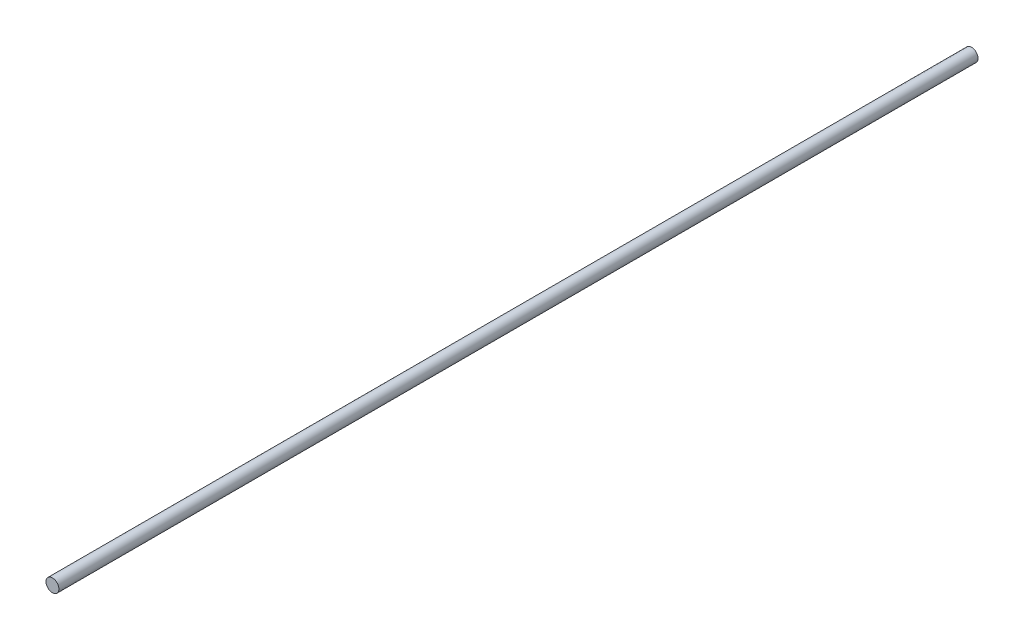
SolidWorks part; units mm, degrees
ref_plane "Ebene vorne" through (0, 0, 0) normal (0, 0, 1) x (1, 0, 0)
ref_plane "Ebene oben" through (0, 0, 0) normal (0, 1, 0) x (1, 0, 0)
ref_plane "Ebene rechts" through (0, 0, 0) normal (1, 0, 0) x (0, 0, -1)
sketch "Skizze1" plane through (0, 0, 0) normal (0, 0, 1) x (1, 0, 0)
  circle A0 centre (0, 0) radius 4
extrude "Aufsatz-Linear austragen1" add sketch "Skizze1" along normal blind 570
cosmetic thread "Gewindedarstellung5" parameters "D2"=6.891
